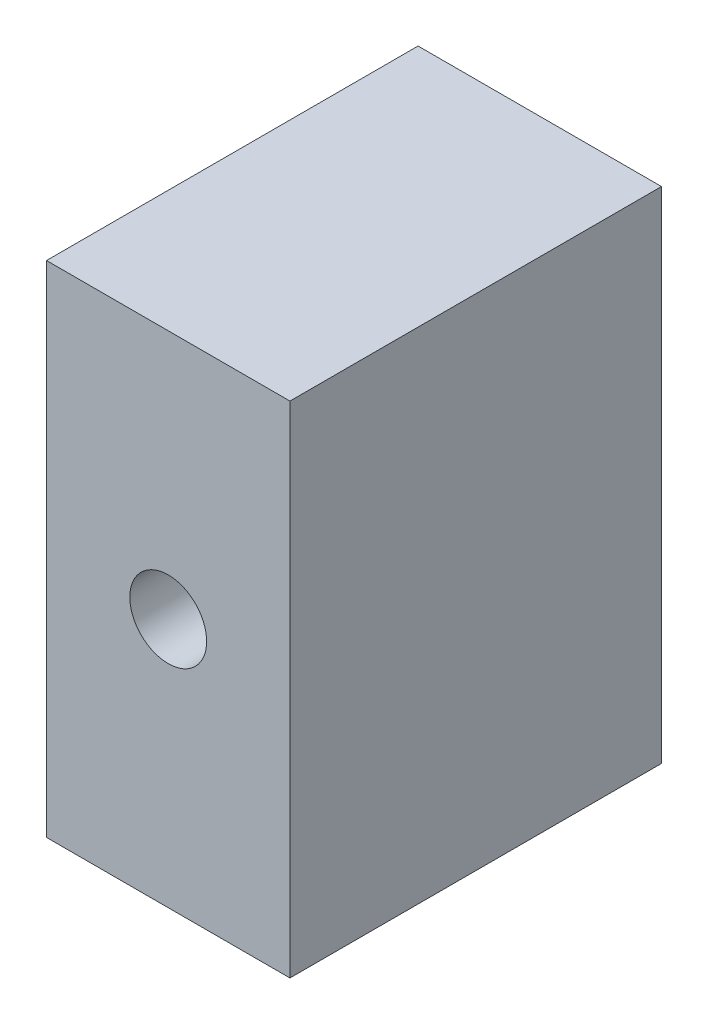
SolidWorks part; units mm, degrees
ref_plane "Plan de face" through (0, 0, 0) normal (0, 0, 1) x (1, 0, 0)
ref_plane "Plan de dessus" through (0, 0, 0) normal (0, 1, 0) x (1, 0, 0)
ref_plane "Plan de droite" through (0, 0, 0) normal (1, 0, 0) x (0, 0, -1)
sketch "Esquisse1" plane through (0, 0, 0) normal (0, 0, 1) x (1, 0, 0)
  line L1 (0, 0) -> (19, 0)
  line L2 (0, 0) -> (0, 39)
  line L3 (0, 39) -> (19, 39)
  line L4 (19, 0) -> (19, 39)
  circle A0 centre (9.5, 19.5) radius 3
  point P7 (0, 0)
  point P8 (9.5, 39)
  point P9 (19, 19.5)
  dimension "D3" = 6
  dimension "D1" = 19
  dimension "D2" = 39
extrude "Boss.-Extru.1" add sketch "Esquisse1" along normal blind 29
